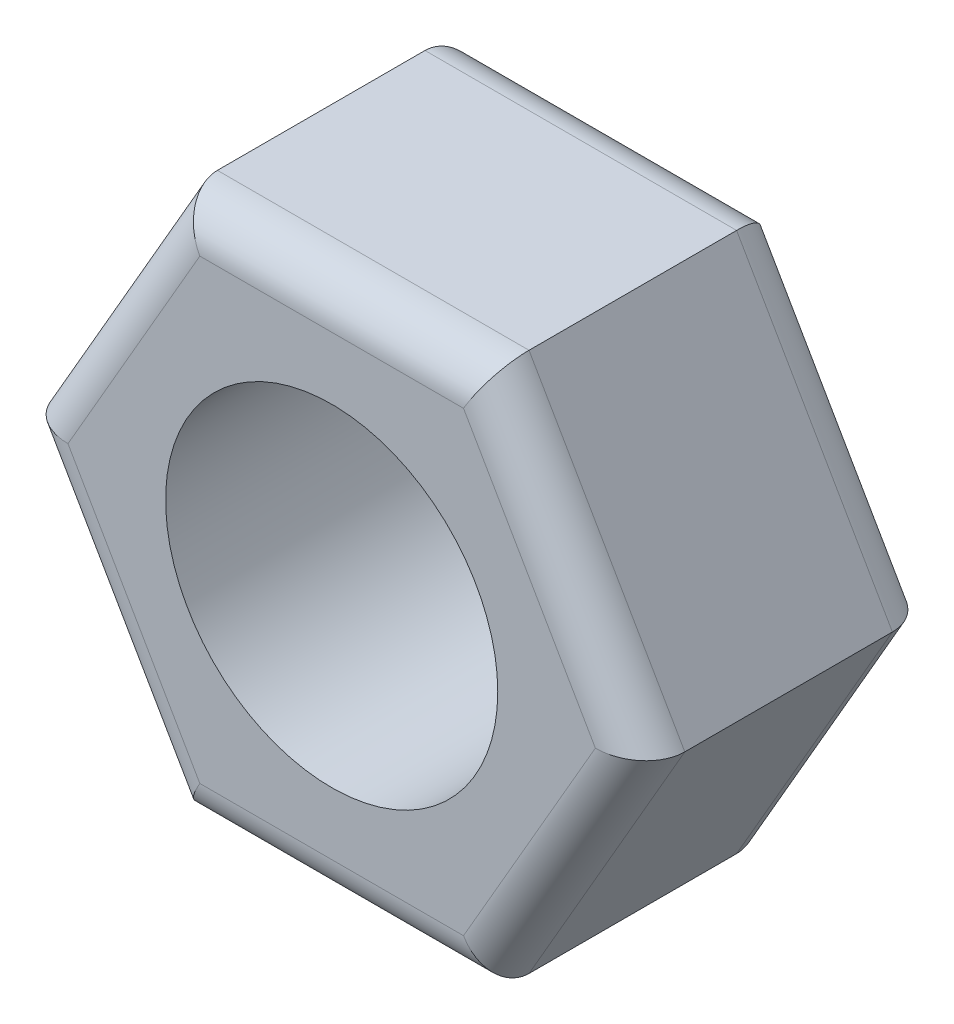
SolidWorks part; units mm, degrees
material "1023 Carbon Steel Sheet (SS)"
ref_plane "Ebene vorne" through (0, 0, 0) normal (0, 0, 1) x (1, 0, 0)
ref_plane "Ebene oben" through (0, 0, 0) normal (0, 1, 0) x (1, 0, 0)
ref_plane "Ebene rechts" through (0, 0, 0) normal (1, 0, 0) x (0, 0, -1)
sketch "Sketch1" plane through (0, 0, 0) normal (0, 0, 1) x (1, 0, 0)
  line L0 (-2.8146, 1.625) -> (-1.8764, 3.25)
  line L1 (-1.8764, 3.25) -> (0, 3.25)
  line L2 (0, 3.25) -> (1.8764, 3.25)
  line L3 (1.8764, 3.25) -> (2.8146, 1.625)
  line L4 (2.8146, 1.625) -> (3.7528, 0)
  line L5 (3.7528, 0) -> (2.8146, -1.625)
  line L6 (2.8146, -1.625) -> (1.8764, -3.25)
  line L7 (1.8764, -3.25) -> (0, -3.25)
  line L8 (0, -3.25) -> (-1.8764, -3.25)
  line L9 (-1.8764, -3.25) -> (-2.8146, -1.625)
  line L10 (-2.8146, -1.625) -> (-3.7528, 0)
  line L11 (-3.7528, 0) -> (-2.8146, 1.625)
  circle A0 centre (0, 0) radius 2
  circle A1 centre (0, 0) radius 3.25 construction
  dimension "D1" = 6.5
  dimension "D2" = 4
extrude "Boss-Extrude1" add sketch "Sketch1" along normal blind 3.5
fillet "Fillet1" radius 0.5 12 edges at (0, -3.25, 0) (2.8146, -1.625, 0) (2.8146, 1.625, 0) (0, 3.25, 0) (-2.8146, 1.625, 0) (-2.8146, -1.625, 0) (0, 3.25, 3.5) (2.8146, 1.625, 3.5) (2.8146, -1.625, 3.5) (0, -3.25, 3.5) (-2.8146, -1.625, 3.5) (-2.8146, 1.625, 3.5)
